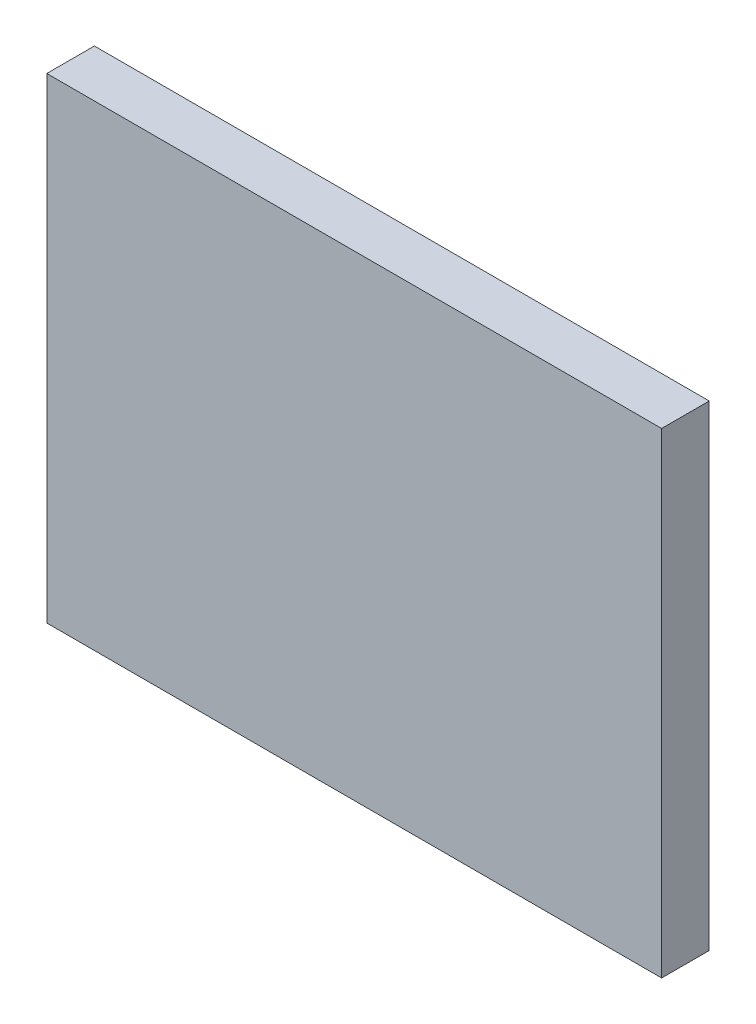
SolidWorks part; units mm, degrees
ref_plane "Plan de face" through (0, 0, 0) normal (0, 0, 1) x (1, 0, 0)
ref_plane "Plan de dessus" through (0, 0, 0) normal (0, 1, 0) x (1, 0, 0)
ref_plane "Plan de droite" through (0, 0, 0) normal (1, 0, 0) x (0, 0, -1)
sketch "Esquisse1" plane through (0, 0, 0) normal (0, 0, 1) x (1, 0, 0)
  line L1 (-32.2973, 25) -> (32.2973, 25)
  line L2 (-32.2973, 25) -> (-32.2973, -25)
  line L3 (-32.2973, -25) -> (32.2973, -25)
  line L4 (32.2973, 25) -> (32.2973, -25)
  line L5 (-32.2973, 25) -> (32.2973, -25) construction
  line L6 (-32.2973, -25) -> (32.2973, 25) construction
  point P0 (0, 0)
  dimension "D1" = 64.5946
  dimension "D2" = 50
extrude "Boss.-Extru.1" add sketch "Esquisse1" along normal blind 5
